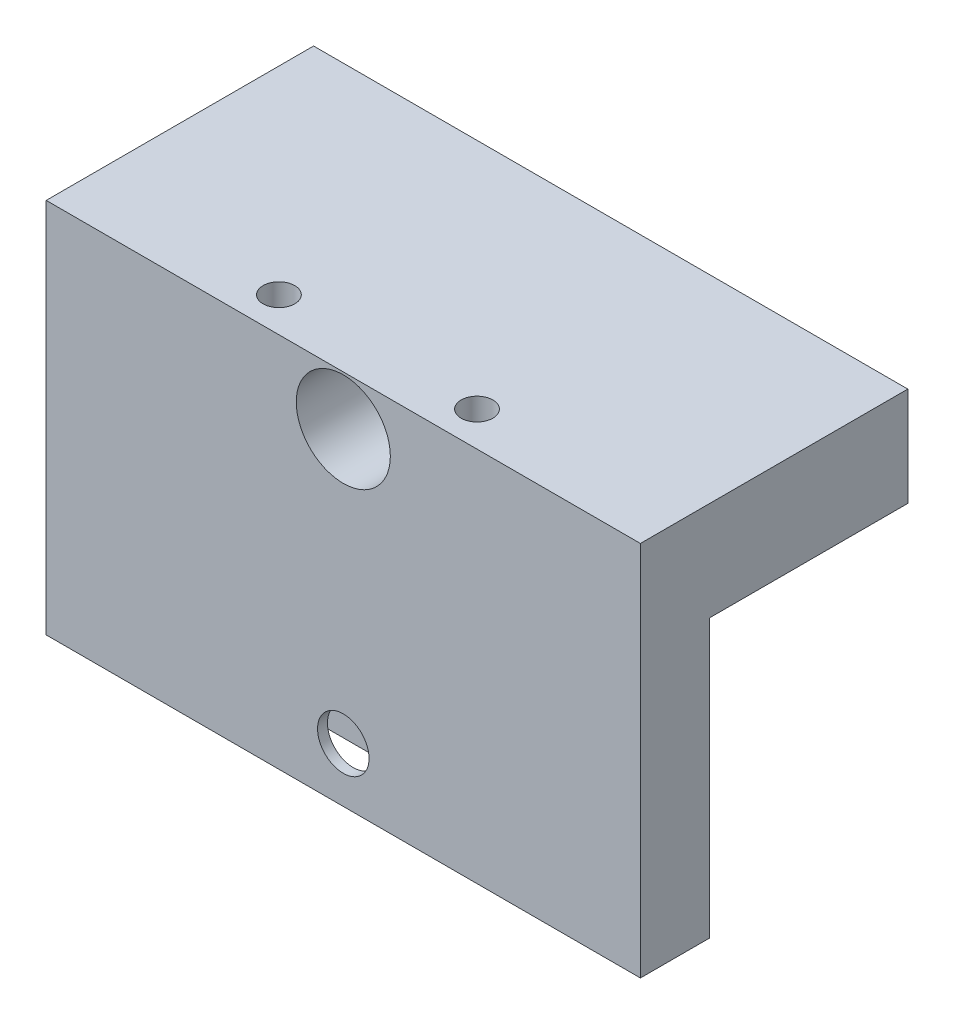
SolidWorks part; units mm, degrees
ref_plane "Front Plane" through (0, 0, 0) normal (0, 0, 1) x (1, 0, 0)
ref_plane "Top Plane" through (0, 0, 0) normal (0, 1, 0) x (1, 0, 0)
ref_plane "Right Plane" through (0, 0, 0) normal (1, 0, 0) x (0, 0, -1)
sketch "Sketch1" plane through (0, 0, 0) normal (0, 1, 0) x (1, 0, 0)
  line L1 (-30, 13.5) -> (30, 13.5)
  line L2 (-30, 13.5) -> (-30, -13.5)
  line L3 (-30, -13.5) -> (30, -13.5)
  line L4 (30, 13.5) -> (30, -13.5)
  line L5 (-30, 13.5) -> (30, -13.5) construction
  line L6 (-30, -13.5) -> (30, 13.5) construction
  point P0 (0, 0)
  dimension "D1" = 60
  dimension "D2" = 27
extrude "Boss-Extrude1" add sketch "Sketch1" along normal blind 10
sketch "Sketch2" plane through (0, 0, 13.5) normal (0, 0, 1) x (1, 0, 0)
  line L0 (-30, 5) -> (30, 5) construction
  line L1 (-30, 10) -> (-30, 0) construction
  line L2 (30, 10) -> (30, 0) construction
  circle A0 centre (0, 5) radius 2.6
  dimension "D1" = 5.2
extrude "Cut-Extrude1" cut sketch "Sketch2" against normal through all
sketch "Sketch3" plane through (0, 0, 13.5) normal (0, 0, 1) x (1, 0, 0)
  circle A0 centre (0, 5) radius 4.75
  dimension "D1" = 9.5
extrude "Cut-Extrude2" cut sketch "Sketch3" against normal offset from surface (22 mm away) 5 up to face at (2.6, 5, -13.5)
sketch "Sketch4" plane through (0, 0, 0) normal (0, -1, 0) x (1, 0, 0)
  line L0 (30, 13.5) -> (30, -13.5) construction
  line L1 (-30, 13.5) -> (30, 13.5)
  line L2 (-30, 13.5) -> (-30, 6.5)
  line L3 (-30, 6.5) -> (30, 6.5)
  line L4 (30, 13.5) -> (30, 6.5)
  line L5 (0, 13.5) -> (0, 6.5) construction
  line L7 (-20, 12.5) -> (20, 12.5)
  line L8 (-20, 12.5) -> (-20, 7.5)
  line L9 (-20, 7.5) -> (20, 7.5)
  line L10 (20, 12.5) -> (20, 7.5)
  line L11 (-20, 12.5) -> (20, 7.5) construction
  line L12 (-20, 7.5) -> (20, 12.5) construction
  point P9 (0, 10)
  dimension "D1" = 7
  dimension "D2" = 40
  dimension "D3" = 5
extrude "Boss-Extrude3" add sketch "Sketch4" along normal blind 28
sketch "Sketch5" plane through (0, 0, 13.5) normal (0, 0, 1) x (1, 0, 0)
  line L0 (30, -28) -> (-30, -28) construction
  circle A0 centre (0, -22.5) radius 2.6
  point P4 (0, -28)
  dimension "D2" = 5.2
  dimension "D3" = 22.5
extrude "Cut-Extrude3" cut sketch "Sketch5" against normal through all
sketch "Sketch6" plane through (0, 10, 0) normal (0, 1, 0) x (1, 0, 0)
  circle A0 centre (-10, -10) radius 1.6
  circle A1 centre (10, -10) radius 1.6
  dimension "D1" = 10
  dimension "D3" = 3.2
  dimension "D2" = 10
  dimension "D5" = 10
extrude "Cut-Extrude4" cut sketch "Sketch6" against normal through all
